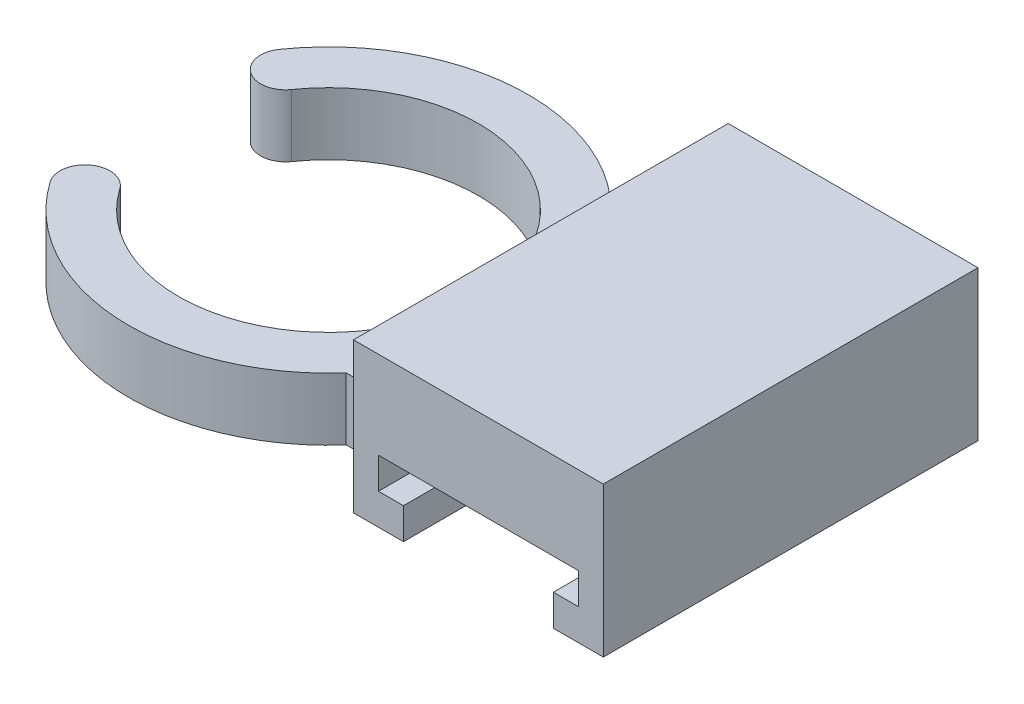
SolidWorks part; units mm, degrees
ref_plane "前视基准面" through (0, 0, 0) normal (0, 0, 1) x (1, 0, 0)
ref_plane "上视基准面" through (0, 0, 0) normal (0, 1, 0) x (1, 0, 0)
ref_plane "右视基准面" through (0, 0, 0) normal (1, 0, 0) x (0, 0, -1)
sketch "草图1" plane through (0, 0, 0) normal (0, 0, 1) x (1, 0, 0)
  line L2 (-19.7321, -1.5982) -> (-11.7321, -1.5982)
  line L3 (-11.7321, -1.5982) -> (-11.7321, 3.4018)
  line L4 (-11.7321, 3.4018) -> (-15.7321, 3.4018)
  line L5 (-15.7321, 3.4018) -> (-15.7321, 8.4018)
  line L6 (-15.7321, 8.4018) -> (16.2679, 8.4018)
  line L7 (0.2679, 8.4018) -> (0.2679, -7.5982) construction
  line L8 (16.2679, 3.4018) -> (16.2679, 8.4018)
  line L9 (12.2679, 3.4018) -> (16.2679, 3.4018)
  line L10 (12.2679, -1.5982) -> (12.2679, 3.4018)
  line L11 (20.2679, -1.5982) -> (12.2679, -1.5982)
  line L13 (-19.7321, -1.5982) -> (-19.7321, 22.4018)
  line L14 (-19.7321, 22.4018) -> (20.2679, 22.4018)
  line L15 (20.2679, 22.4018) -> (20.2679, -1.5982)
extrude "凸台-拉伸1" add sketch "草图1" along normal blind 60
sketch "草图2" plane through (0, -1.5982, 0) normal (0, -1, 0) x (1, 0, 0)
  line L4 (-29.7321, 51.166) -> (-19.7321, 51.166)
  line L5 (-19.7321, 60) -> (-19.7321, 0) construction
  line L6 (-19.7321, 51.166) -> (-19.7321, 8.834)
  line L7 (-19.7321, 8.834) -> (-29.7321, 8.834)
  arc A0 (-73.3918, 16.2342) -> (-73.3918, 43.7658) centre (-53.7321, 30) ccw
  arc A1 (-79.945, 11.6456) -> (-29.7321, 8.834) centre (-53.7321, 30) ccw
  arc A2 (-79.945, 48.3544) -> (-73.3918, 43.7658) centre (-76.6684, 46.0601) ccw
  arc A3 (-79.945, 11.6456) -> (-73.3918, 16.2342) centre (-76.6684, 13.9399) cw
  arc A4 (-29.7321, 51.166) -> (-79.945, 48.3544) centre (-53.7321, 30) ccw
  line M10 (-19.7321, 60) -> (-19.7321, 0)
extrude "凸台-拉伸2" add sketch "草图2" against normal blind 10 contours A3 A1 A0 M10 | A4 A2 A0 M10
